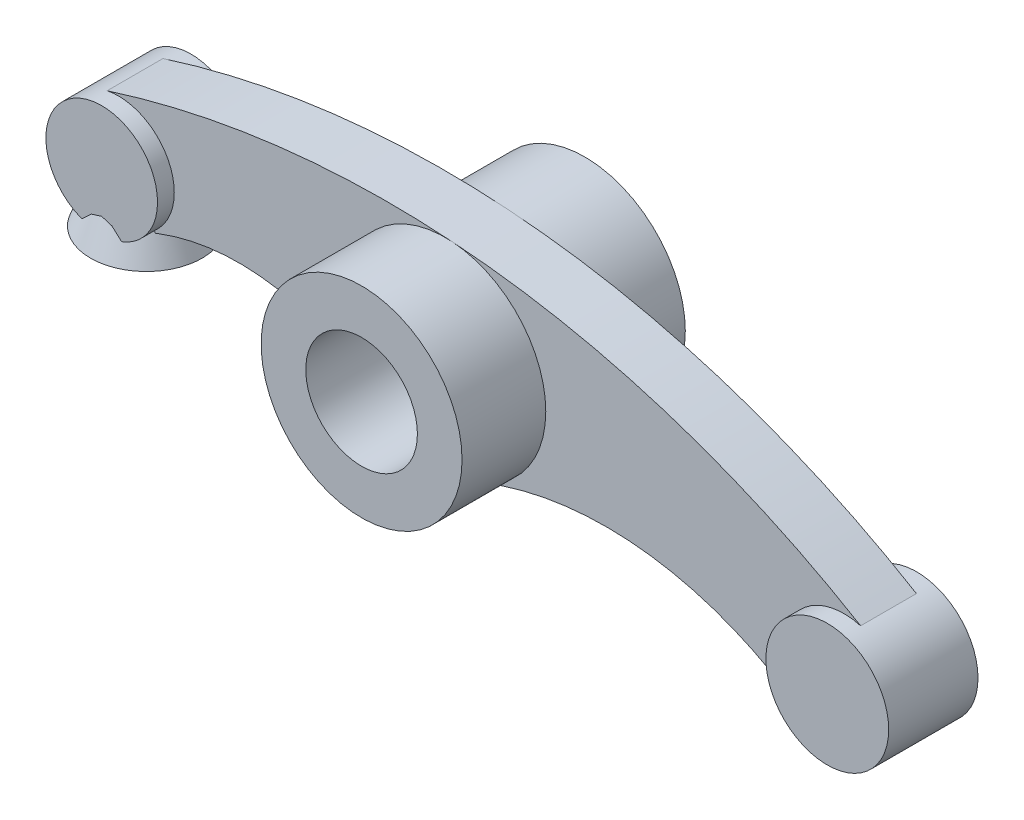
SolidWorks part; units mm, degrees
ref_plane "Front Plane" through (0, 0, 0) normal (0, 0, 1) x (1, 0, 0)
ref_plane "Top Plane" through (0, 0, 0) normal (0, 1, 0) x (1, 0, 0)
ref_plane "Right Plane" through (0, 0, 0) normal (1, 0, 0) x (0, 0, -1)
sketch "Sketch1" plane through (0, 0, 0) normal (0, 0, 1) x (1, 0, 0)
  line L0 (-34.2802, 0.3388) -> (-34.2802, 41.9011) construction
  line L1 (41.2198, -7.8215) -> (41.2198, 38.8739) construction
  line L2 (-5.1145, 9.1785) -> (95.768, 9.1785) construction
  line L3 (35.7198, -13.3215) -> (112.4729, -13.3215) construction
  circle A0 centre (0, 0) radius 5
  arc A1 (-6.6025, -6.1161) -> (3.3492, -8.3536) centre (0, 0) ccw
  arc A2 (32.4218, -12.223) -> (37.2052, -2.5259) centre (35.7198, -7.8215) ccw
  arc A5 (-30.2955, 5.2346) -> (-27.12, -4.1705) centre (-29.2802, 0.3388) ccw
  arc A6 (-31.3675, 4.8822) -> (37.2052, -2.5259) centre (-5.1145, -73.1815) cw
  arc A7 (32.4218, -12.223) -> (3.3121, -8.3684) centre (14.4327, -36.2311) ccw
  arc A8 (-27.12, -4.1705) -> (-4.8143, -7.6041) centre (-18.4794, -22.2077) cw
  dimension "D1" = 10
  dimension "D2" = 18
  dimension "D3" = 11
  dimension "D4" = 10
  dimension "D5" = 82.36
  dimension "D6" = 75.5
  dimension "D9" = 30
  dimension "D10" = 20
  dimension "D7" = 22.5
  dimension "D8" = 14.4327
extrude "Boss-Extrude1" add sketch "Sketch1" along normal mid plane 5 contours A5 A8 A1 A7 A2 A6 A0
sketch "Sketch2" plane through (0, 0, 0) normal (0, 0, 1) x (1, 0, 0)
  circle A0 centre (0, 0) radius 9
  circle A1 centre (0, 0) radius 5
extrude "Boss-Extrude2" add sketch "Sketch2" along normal mid plane 20
sketch "Sketch3" plane through (0, 0, 0) normal (0, 0, 1) x (1, 0, 0)
  circle A0 centre (35.7198, -7.8215) radius 5.5
  circle A1 centre (-29.2802, 0.3388) radius 5
extrude "Boss-Extrude3" add sketch "Sketch3" along normal mid plane 8
ref_plane "Plane1" through (0, -6, 0) normal (0, 1, 0) x (1, 0, 0)
sketch "Sketch4" plane through (0, -6, 0) normal (0, 1, 0) x (1, 0, 0)
  circle A0 centre (-29.2802, 0) radius 5
  dimension "D1" = 10
extrude "Boss-Extrude4" add sketch "Sketch4" along normal blind 7 draft 20 separate body contours A0
ref_plane "Plane2" through (0, -13.3215, 0) normal (0, -1, 0) x (-1, 0, 0)
sketch "Sketch5" plane through (0, -13.3215, 0) normal (0, -1, 0) x (-1, 0, 0)
  circle A0 centre (-35.7198, 0) radius 2
  dimension "D1" = 4
